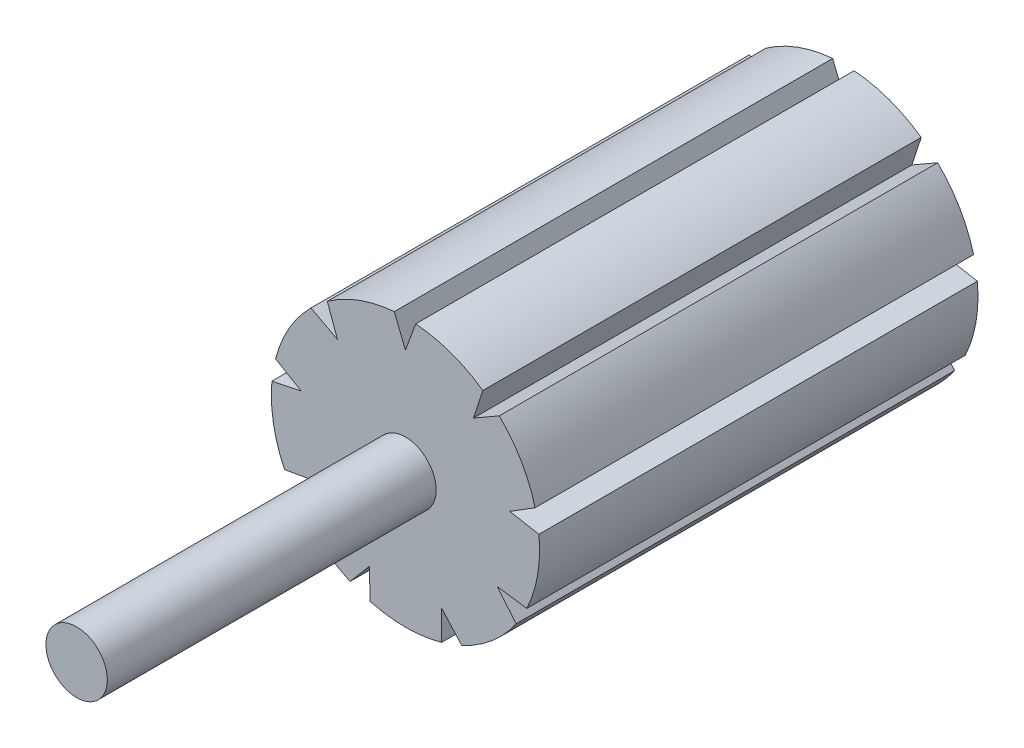
SolidWorks part; units mm, degrees
material "Ductile Iron"
ref_plane "Front Plane" through (0, 0, 0) normal (0, 0, 1) x (1, 0, 0)
ref_plane "Top Plane" through (0, 0, 0) normal (0, 1, 0) x (1, 0, 0)
ref_plane "Right Plane" through (0, 0, 0) normal (1, 0, 0) x (0, 0, -1)
sketch "Sketch1" plane through (0, 0, 0) normal (0, 0, 1) x (1, 0, 0)
  line L0 (3.1026, 3.6976) -> (4.2796, 4.3732)
  line L1 (0, 4.8268) -> (0.4673, 6.101)
  line L3 (-0.51, 6.0975) -> (0, 4.8268)
  line L4 (3.5287, 4.9988) -> (3.1026, 3.6976)
  line L5 (4.7535, 0.8382) -> (6.0894, 0.5992)
  line L6 (5.9163, 1.5611) -> (4.7535, 0.8382)
  line L7 (4.1802, -2.4134) -> (5.0499, -3.4552)
  line L8 (5.5356, -2.6071) -> (4.1802, -2.4134)
  line L9 (1.6509, -4.5358) -> (1.6475, -5.8929)
  line L10 (2.5647, -5.5554) -> (1.6509, -4.5358)
  line L11 (-1.6509, -4.5358) -> (-2.5258, -5.5732)
  line L12 (-1.6062, -5.9042) -> (-1.6509, -4.5358)
  line L13 (-4.1802, -2.4134) -> (-5.5173, -2.6458)
  line L14 (-5.0256, -3.4904) -> (-4.1802, -2.4134)
  line L15 (-4.7535, 0.8382) -> (-5.9271, 1.5197)
  line L16 (-6.0935, 0.5566) -> (-4.7535, 0.8382)
  line L17 (-3.1026, 3.6976) -> (-3.5636, 4.974)
  line L18 (-4.3101, 4.3432) -> (-3.1026, 3.6976)
  arc A1 (-0.51, 6.0975) -> (-3.5636, 4.974) centre (0, 0) ccw
  arc A2 (3.5287, 4.9988) -> (0.4673, 6.101) centre (0, 0) ccw
  arc A3 (5.9163, 1.5611) -> (4.2796, 4.3732) centre (0, 0) ccw
  arc A4 (5.5356, -2.6071) -> (6.0894, 0.5992) centre (0, 0) ccw
  arc A5 (2.5647, -5.5554) -> (5.0499, -3.4552) centre (0, 0) ccw
  arc A6 (-1.6062, -5.9042) -> (1.6475, -5.8929) centre (0, 0) ccw
  arc A7 (-5.0256, -3.4904) -> (-2.5258, -5.5732) centre (0, 0) ccw
  arc A8 (-6.0935, 0.5566) -> (-5.5173, -2.6458) centre (0, 0) ccw
  arc A9 (-4.3101, 4.3432) -> (-5.9271, 1.5197) centre (0, 0) ccw
  point P32 (0, 0)
  dimension "D1" = 12.2377
  dimension "D2" = 9
extrude "Boss-Extrude1" add sketch "Sketch1" along normal blind 20
sketch "Sketch2" plane through (0, 0, 20) normal (0, 0, 1) x (1, 0, 0)
  circle A0 centre (0, 0) radius 1.4003
extrude "Boss-Extrude3" add sketch "Sketch2" along normal blind 15
